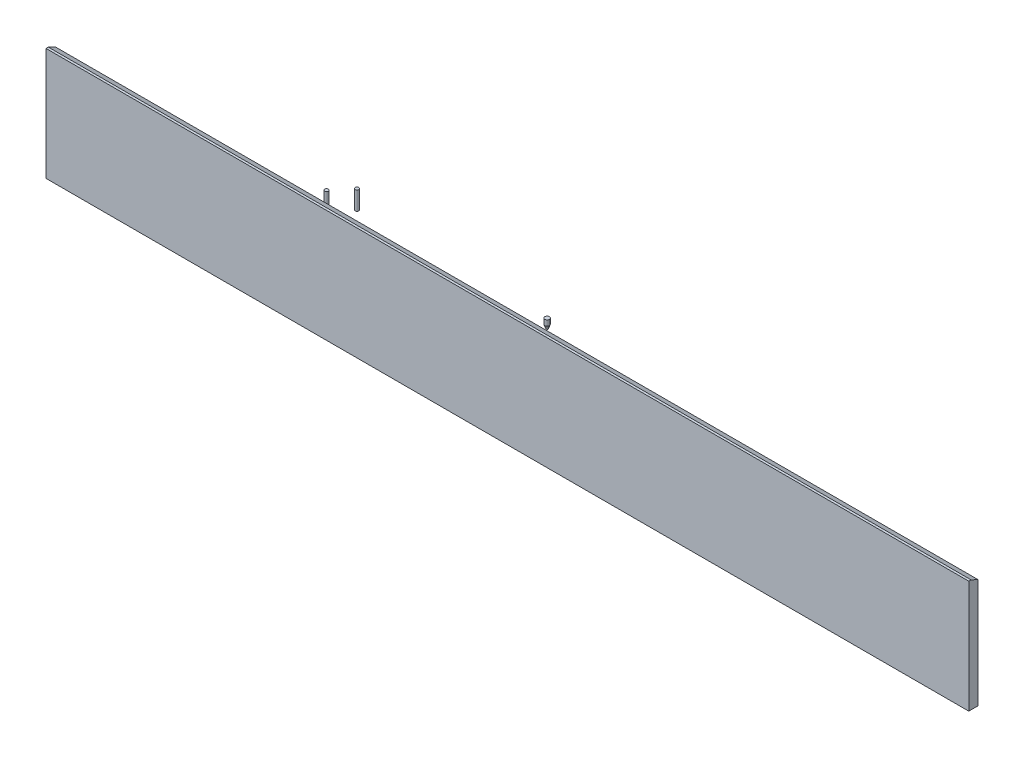
SolidWorks part; units mm, degrees
ref_plane "Front Plane" through (0, 0, 0) normal (0, 0, 1) x (1, 0, 0)
ref_plane "Top Plane" through (0, 0, 0) normal (0, 1, 0) x (1, 0, 0)
ref_plane "Right Plane" through (0, 0, 0) normal (1, 0, 0) x (0, 0, -1)
sketch "Sketch1" plane through (0, 0, 0) normal (0, 0, 1) x (1, 0, 0)
  line L1 (500, 61) -> (-500, 61)
  line L2 (500, 61) -> (500, -61)
  line L3 (500, -61) -> (-500, -61)
  line L4 (-500, 61) -> (-500, -61)
  line L5 (500, 61) -> (-500, -61) construction
  line L6 (500, -61) -> (-500, 61) construction
  point P0 (0, 0)
  dimension "D1" = 1000
  dimension "D2" = 122
extrude "Board" add sketch "Sketch1" along normal blind 10
chamfer "Board chamfer" distance 3.5 angle 65 1 edges at (0, 61, 0)
sketch "Sketch2" plane through (0, 0, 0) normal (0, 1, 0) x (1, 0, 0)
  line L0 (-500, 0) -> (500, 0) construction
  circle A0 centre (0, 33) radius 2.5
  circle A1 centre (-22, 10) radius 2.5
  dimension "D2" = 5
  dimension "D1" = 33
  dimension "D3" = 10
  dimension "D4" = 22
extrude "Dynafit" add sketch "Sketch2" along normal blind 10 from offset 26.5 separate body
chamfer "Dynafit pin chamfer" distance 1.5 angle 70 1 edges at (0, 26.5, -30.5)
sketch "Sketch5" plane through (0, 0, 0) normal (0, 1, 0) x (1, 0, 0)
  line L0 (-500, 0) -> (500, 0) construction
  line L1 (-276, 14) -> (-221, 14)
  line L2 (-276, 14) -> (-276, 0)
  line L3 (-276, 0) -> (-156, 0)
  line L4 (-156, 14) -> (-156, 0)
  line L5 (-221, 16) -> (-221, 14)
  line L6 (-217, 14) -> (-191, 14)
  line L7 (-217, 16) -> (-217, 14)
  line L8 (-187, 14) -> (-156, 14)
  line L9 (-191, 16) -> (-191, 14)
  line L11 (-187, 16) -> (-187, 14)
  arc A0 (-187, 16) -> (-191, 16) centre (-189, 16) ccw
  arc A1 (-217, 16) -> (-221, 16) centre (-219, 16) ccw
  circle A2 centre (-266, 60) radius 2
  circle A3 centre (-251, 78) radius 2
  dimension "D4" = 4
  dimension "D1" = 120
  dimension "D2" = 276
  dimension "D3" = 14
  dimension "D5" = 57
  dimension "D6" = 87
  dimension "D7" = 60
  dimension "D8" = 78
  dimension "D9" = 25
  dimension "D10" = 10
extrude "Riser " add sketch "Sketch5" along normal mid plane 20
